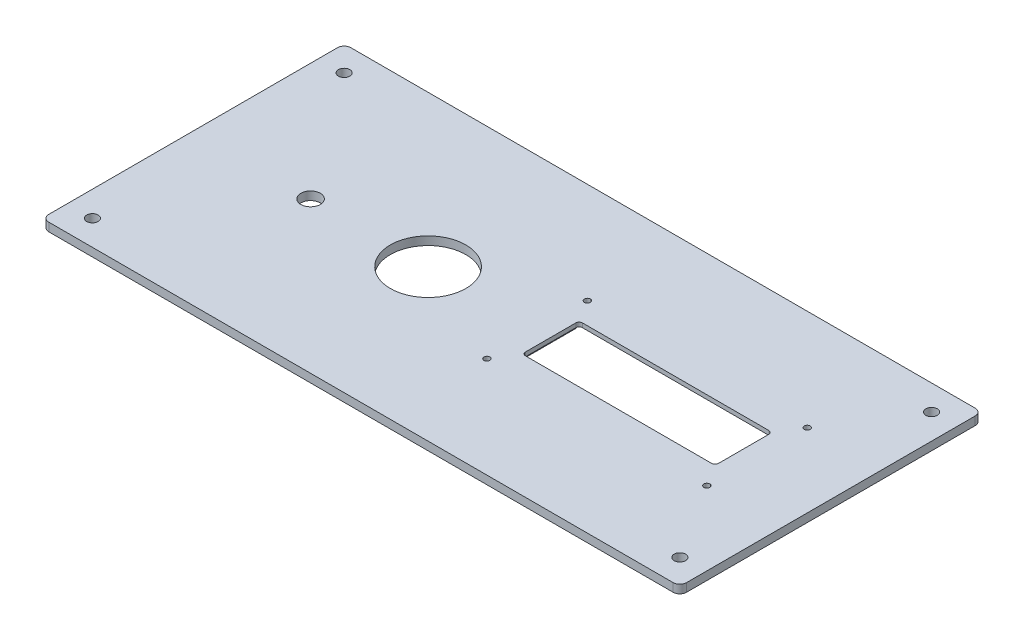
SolidWorks part; units mm, degrees
ref_plane "Front Plane" through (0, 0, 0) normal (0, 0, 1) x (1, 0, 0)
ref_plane "Top Plane" through (0, 0, 0) normal (0, 1, 0) x (1, 0, 0)
ref_plane "Right Plane" through (0, 0, 0) normal (1, 0, 0) x (0, 0, -1)
sketch "Sketch1" plane through (0, 0, 0) normal (0, 1, 0) x (1, 0, 0)
  line L0 (0, 57.15) -> (0, -57.15) construction
  line L1 (-120.65, -57.15) -> (120.65, -57.15)
  line L2 (-120.65, -57.15) -> (-120.65, 57.15)
  line L3 (-120.65, 57.15) -> (120.65, 57.15)
  line L4 (120.65, -57.15) -> (120.65, 57.15)
  line L5 (-120.65, -57.15) -> (120.65, 57.15) construction
  line L6 (-120.65, 57.15) -> (120.65, -57.15) construction
  line L7 (-120.65, 0) -> (120.65, 0) construction
  line L8 (51.1175, 0) -> (51.1175, 31.2134) construction
  line L9 (14.605, -10.795) -> (87.63, -10.795)
  line L10 (14.605, -10.795) -> (14.605, 10.795)
  line L11 (14.605, 10.795) -> (87.63, 10.795)
  line L12 (87.63, -10.795) -> (87.63, 10.795)
  line L13 (14.605, -10.795) -> (87.63, 10.795) construction
  line L14 (14.605, 10.795) -> (87.63, -10.795) construction
  circle A0 centre (-111.125, 47.625) radius 2.159
  circle A1 centre (111.125, 47.625) radius 2.159
  circle A2 centre (111.125, -47.625) radius 2.159
  circle A3 centre (-111.125, -47.625) radius 2.159
  circle A4 centre (-76.2, 0) radius 3.683
  circle A5 centre (-31.75, 0) radius 14.2875
  circle A6 centre (9.5175, 19) radius 1.1303
  circle A7 centre (9.5175, -19) radius 1.1303
  circle A8 centre (92.7175, -19) radius 1.1303
  circle A9 centre (92.7175, 19) radius 1.1303
  point P0 (0, 0)
  point P22 (51.1175, 0)
  dimension "D5" = 4.318
  dimension "D6" = 28.575
  dimension "D7" = 7.366
  dimension "D15" = 2.2606
  dimension "D1" = 241.3
  dimension "D2" = 114.3
  dimension "D3" = 9.525
  dimension "D4" = 9.525
  dimension "D8" = 21.59
  dimension "D9" = 73.025
  dimension "D10" = 33.02
  dimension "D11" = 88.9
  dimension "D12" = 44.45
  dimension "D13" = 41.6
  dimension "D14" = 19
extrude "Boss-Extrude1" add sketch "Sketch1" along normal blind 3.175
fillet "Fillet1" radius 1.27 4 edges at (87.63, 1.5875, -10.795) (87.63, 1.5875, 10.795) (14.605, 1.5875, 10.795) (14.605, 1.5875, -10.795)
fillet "Fillet2" radius 2.54 4 edges at (-120.65, 1.5875, -57.15) (-120.65, 1.5875, 57.15) (120.65, 1.5875, -57.15) (120.65, 1.5875, 57.15)
sketch "Sketch2" plane through (0, 0, 0) normal (0, -1, 0) x (-1, 0, 0)
  line L0 (-14.605, 9.525) -> (-14.605, -9.525) construction
  line L1 (-88.9635, -12.573) -> (-13.2715, -12.573)
  line L2 (-88.9635, -12.573) -> (-88.9635, 12.573)
  line L3 (-88.9635, 12.573) -> (-13.2715, 12.573)
  line L4 (-13.2715, -12.573) -> (-13.2715, 12.573)
  line L5 (-88.9635, -12.573) -> (-13.2715, 12.573) construction
  line L6 (-88.9635, 12.573) -> (-13.2715, -12.573) construction
  circle A0 centre (-88.9635, 12.573) radius 1.5875
  circle A1 centre (-88.9635, -12.573) radius 1.5875
  circle A2 centre (-13.2715, -12.573) radius 1.5875
  circle A3 centre (-13.2715, 12.573) radius 1.5875
  point P0 (-51.1175, 0)
  line M17 (-14.605, 9.525) -> (-14.605, -9.525)
  arc M18 (-14.605, -9.525) -> (-15.875, -10.795) centre (-15.875, -9.525) cw
  line M19 (-15.875, -10.795) -> (-86.36, -10.795)
  arc M20 (-86.36, -10.795) -> (-87.63, -9.525) centre (-86.36, -9.525) cw
  line M21 (-87.63, -9.525) -> (-87.63, 9.525)
  arc M22 (-87.63, 9.525) -> (-86.36, 10.795) centre (-86.36, 9.525) cw
  line M23 (-86.36, 10.795) -> (-15.875, 10.795)
  arc M24 (-15.875, 10.795) -> (-14.605, 9.525) centre (-15.875, 9.525) cw
  dimension "D4" = 3.175
  dimension "D5" = 3.175
  dimension "D6" = 3.175
  dimension "D7" = 3.175
  dimension "D1" = 36.5125
  dimension "D2" = 25.146
  dimension "D3" = 75.692
extrude "Cut-Extrude1" cut sketch "Sketch2" against normal blind 1.5875 contours A3 L3 A0 L2 A1 L1 A2 L4 M24 M17 M18 M19 M20 M21 M22 M23 | L1 A1 L2 | L2 A1 L1 | L3 A0 L2 | L2 A0 L3 | L4 A3 L3 | L3 A3 L4 | L4 A2 L1 | L1 A2 L4
